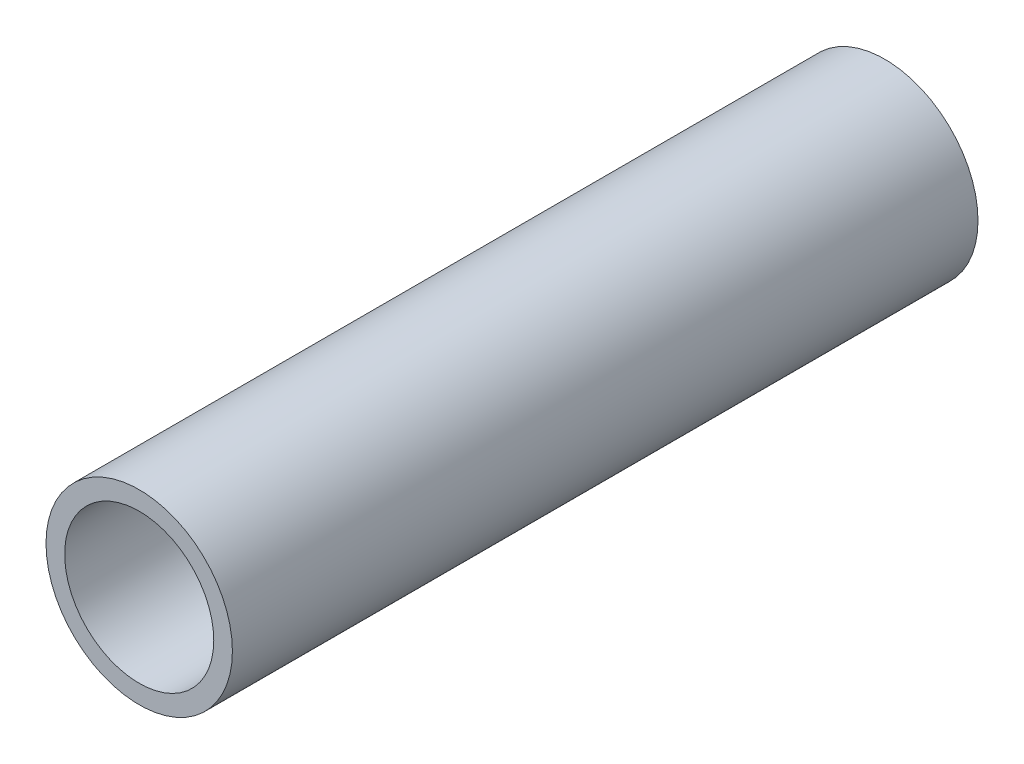
SolidWorks part; units mm, degrees
ref_plane "Front Plane" through (0, 0, 0) normal (0, 0, 1) x (1, 0, 0)
ref_plane "Top Plane" through (0, 0, 0) normal (0, 1, 0) x (1, 0, 0)
ref_plane "Right Plane" through (0, 0, 0) normal (1, 0, 0) x (0, 0, -1)
sketch "Sketch1" plane through (0, 0, 0) normal (0, 0, 1) x (1, 0, 0)
  circle A2 centre (0, 0) radius 10
  circle A3 centre (0, 0) radius 12.5
  dimension "D1" = 25
  dimension "D2" = 20
extrude "Boss-Extrude1" add sketch "Sketch1" against normal blind 100
